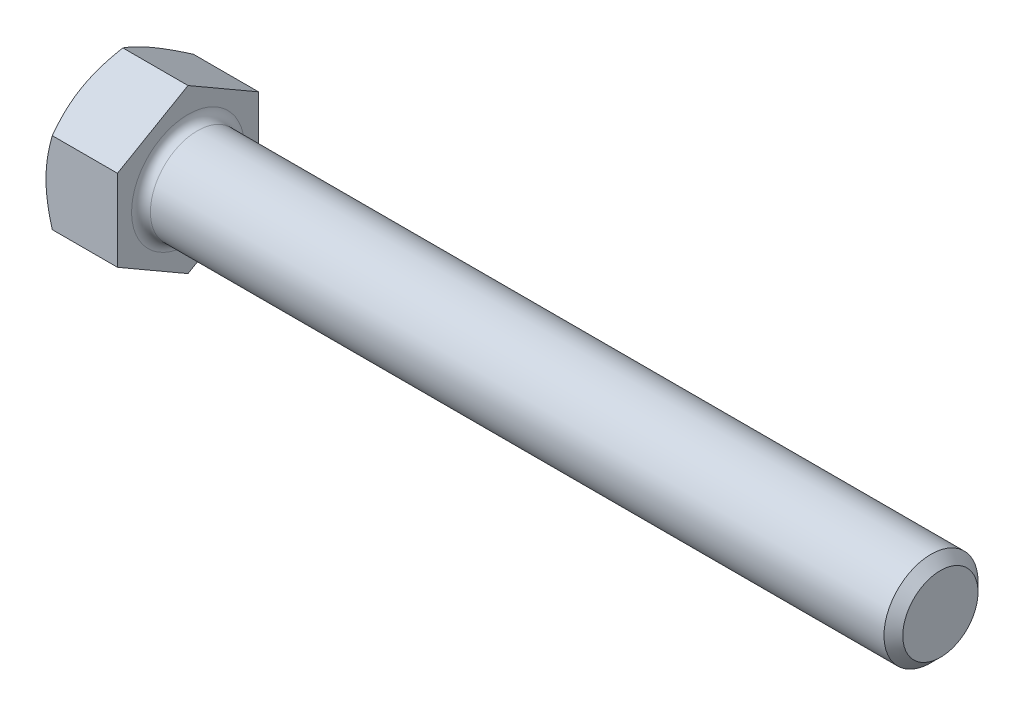
SolidWorks part; units mm, degrees
ref_plane "Front Plane" through (0, 0, 0) normal (0, 0, 1) x (1, 0, 0)
ref_plane "Top Plane" through (0, 0, 0) normal (0, 1, 0) x (1, 0, 0)
ref_plane "Right Plane" through (0, 0, 0) normal (1, 0, 0) x (0, 0, -1)
ref_plane "Plane1"
sketch "Sketch1" plane through (0, 0, 0) normal (0, 0, 1) x (1, 0, 0)
  line L0 (50.8, 0) -> (50.8, 3.175)
  line L1 (50.8, 3.175) -> (0, 3.175)
  line L2 (0, 3.175) -> (0, 0)
  line L3 (0, 0) -> (50.8, 0)
  line L4 (50.8, 0) -> (0, 0) construction
  dimension "D1" = 90
  dimension "D2" = 50.8
revolve "Body" add sketch "Sketch1" angle 360 about L4
cosmetic thread "Cosmetic Thread1" parameters "D1"=50.0202, "D2"=4.8387
sketch "Sketch2" plane through (0, 0, 0) normal (-1, 0, 0) x (0, 0, 1)
  line L0 (0, 5.4993) -> (4.7625, 2.7496)
  line L1 (4.7625, 2.7496) -> (4.7625, -2.7496)
  line L2 (4.7625, -2.7496) -> (0, -5.4993)
  line L3 (0, -5.4993) -> (-4.7625, -2.7496)
  line L4 (-4.7625, -2.7496) -> (-4.7625, 2.7496)
  line L5 (-4.7625, 2.7496) -> (0, 5.4993)
  dimension "D1" = 9.525
extrude "Head" add sketch "Sketch2" along normal blind 4.826
ref_plane "Plane2"
sketch "Sketch3" plane through (0, 0, 0) normal (0, 0, 1) x (1, 0, 0)
  line L0 (-4.826, 4.7625) -> (-4.2761, 5.715)
  line L1 (-4.2761, 5.715) -> (-4.826, 5.715)
  line L2 (-4.826, 5.715) -> (-4.826, 4.7625)
  line L3 (-1.1, 0) -> (-0.234, 0) construction
  line L5 (0, 2.7496) -> (0, 5.4993) construction
  dimension "D1" = 60
  dimension "D2" = 60
  dimension "D3" = 30
revolve "Thread" cut sketch "Sketch3" angle 360 about L3
chamfer "Chamfer2" distance 0.635 distance2 0.6351 1 edges at (50.8, 3.175, 0)
fillet "Fillet" radius 0.635 1 edges at (0, 3.175, 0)
